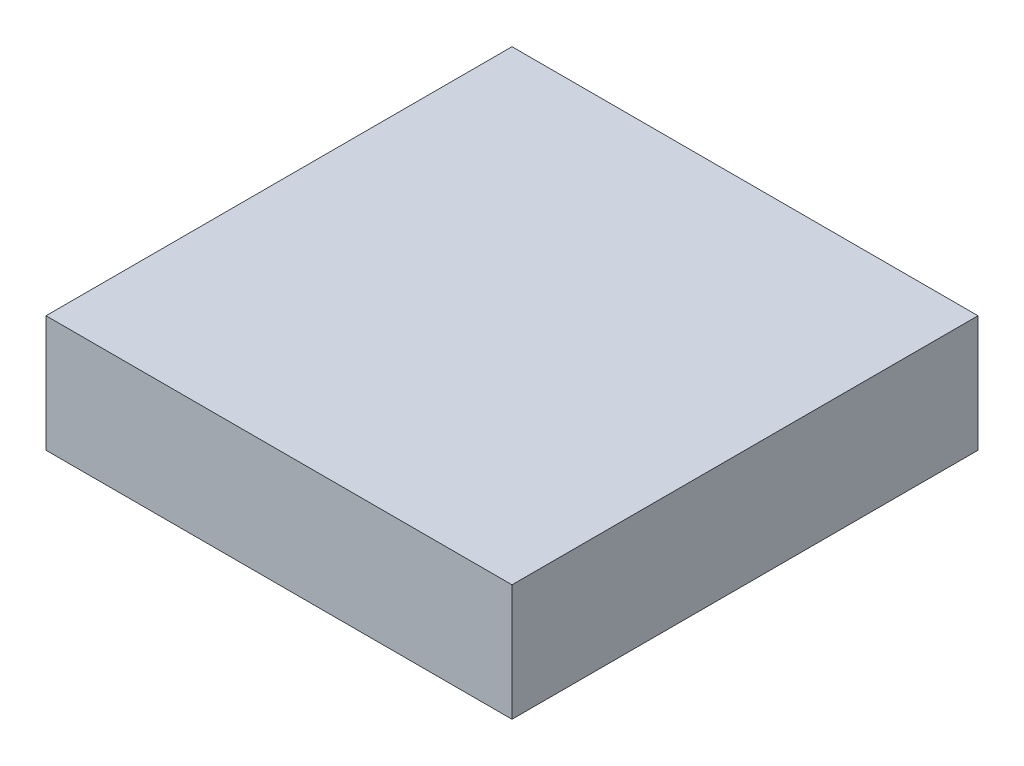
SolidWorks part; units mm, degrees
material "ABS"
ref_plane "Спереди" through (0, 0, 0) normal (0, 0, 1) x (1, 0, 0)
ref_plane "Сверху" through (0, 0, 0) normal (0, 1, 0) x (1, 0, 0)
ref_plane "Справа" through (0, 0, 0) normal (1, 0, 0) x (0, 0, -1)
sketch "Эскиз1" plane through (0, 0, 0) normal (0, 1, 0) x (1, 0, 0)
  line L1 (-12, -12) -> (12, -12)
  line L2 (-12, -12) -> (-12, 12)
  line L3 (-12, 12) -> (12, 12)
  line L4 (12, -12) -> (12, 12)
  line L5 (-12, -12) -> (12, 12) construction
  line L6 (-12, 12) -> (12, -12) construction
  point P0 (0, 0)
  dimension "D1" = 24
  dimension "D2" = 24
extrude "Бобышка-Вытянуть1" add sketch "Эскиз1" along normal blind 6
